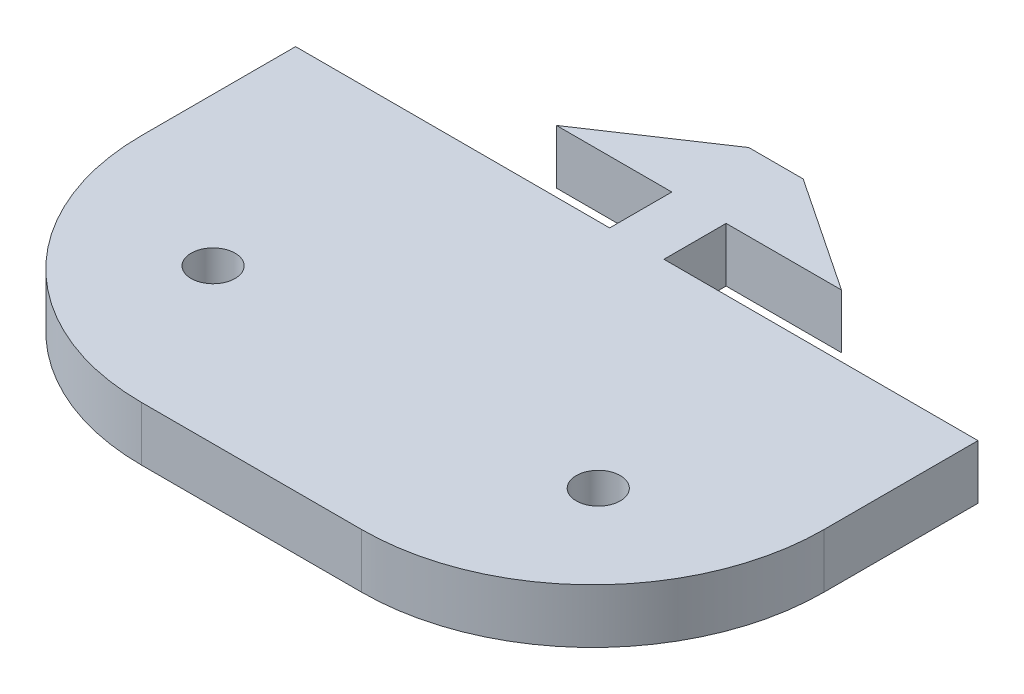
SolidWorks part; units mm, degrees
ref_plane "Front" through (0, 0, 0) normal (0, 0, 1) x (1, 0, 0)
ref_plane "Top" through (0, 0, 0) normal (0, 1, 0) x (1, 0, 0)
ref_plane "Right" through (0, 0, 0) normal (1, 0, 0) x (0, 0, -1)
sketch "Sketch1" plane through (0, 0, 0) normal (0, 1, 0) x (1, 0, 0)
  line L0 (-1.7907, 2.05) -> (-9.398, 2.05)
  line L2 (-1.7907, -2.05) -> (-1.7907, 2.05)
  line L4 (1.7907, -2.05) -> (1.7907, 2.05)
  line L7 (-9.398, 2.05) -> (-1.7907, 7.13)
  line L8 (-1.7907, 7.13) -> (1.7907, 7.13)
  line L9 (1.7907, 7.13) -> (9.398, 2.05)
  line L10 (9.398, 2.05) -> (1.7907, 2.05)
  line L11 (1.7907, -2.05) -> (22.5, -2.05)
  line L12 (-1.7907, -2.05) -> (-22.5, -2.05)
  line L13 (-22.5, -2.05) -> (-22.5, -27.45)
  line L14 (-22.5, -27.45) -> (22.5, -27.45)
  line L15 (22.5, -27.45) -> (22.5, -2.05)
  line L16 (22.5, -2.05) -> (1.7907, -2.05)
  point P0 (0, 0)
  point P17 (0, 7.13)
  point P19 (0, -27.45)
  point P24 (1.7907, 0)
  dimension "D1" = 18.796
  dimension "D2" = 3.5814
  dimension "D3" = 45
  dimension "D4" = 25.4
  dimension "D5" = 5.08
  dimension "D7" = 4.1
extrude "Boss-Extrude1" add sketch "Sketch1" along normal blind 3.5814 contours L14 L15 L11 L4 L10 L9 L8 L7 L0 L2 L12 L13
sketch "Sketch2" plane through (0, 3.5814, 0) normal (0, 1, 0) x (1, 0, 0)
  line L0 (0, 0) -> (0, -15.3387) construction
  line L1 (1.7907, -2.05) -> (22.5, -2.05) construction
  circle A0 centre (-12.7, -17.29) radius 1.45
  circle A1 centre (12.7, -17.29) radius 1.45
  dimension "D1" = 2.9
  dimension "D2" = 12.7
  dimension "D3" = 15.24
extrude "Cut-Extrude1" cut sketch "Sketch2" against normal through all
fillet "Fillet1" radius 15.24 2 edges at (-22.5, 1.7907, 27.45) (22.5, 1.7907, 27.45)
